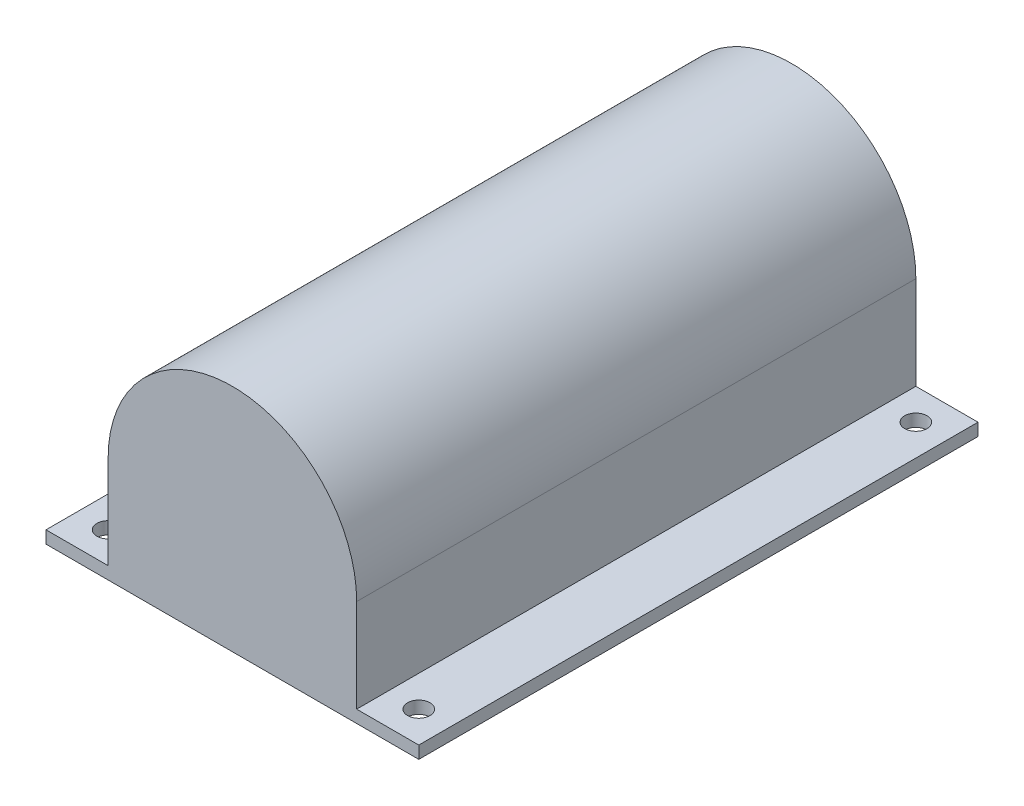
SolidWorks part; units mm, degrees
ref_plane "Front Plane" through (0, 0, 0) normal (0, 0, 1) x (1, 0, 0)
ref_plane "Top Plane" through (0, 0, 0) normal (0, 1, 0) x (1, 0, 0)
ref_plane "Right Plane" through (0, 0, 0) normal (1, 0, 0) x (0, 0, -1)
sketch "Sketch1" plane through (0, 0, 0) normal (0, 0, 1) x (1, 0, 0)
  line L0 (38.1, 8.89) -> (38.1, 46.99) construction
  line L1 (0, 0) -> (76.2, 0)
  line L2 (0, 0) -> (0, 2.54)
  line L3 (0, 2.54) -> (12.7, 2.54)
  line L4 (76.2, 0) -> (76.2, 2.54)
  line L5 (12.7, 2.54) -> (12.7, 21.59)
  line L7 (63.5, 21.59) -> (63.5, 2.54)
  line L10 (63.5, 2.54) -> (76.2, 2.54)
  arc A1 (63.5, 21.59) -> (12.7, 21.59) centre (38.1, 21.59) ccw
  point P8 (38.1, 2.54)
  dimension "D5" = 25.4
  dimension "D3" = 19.05
  dimension "D1" = 76.2
  dimension "D2" = 2.54
  dimension "D4" = 38.1
  dimension "D6" = 12.7
  dimension "D7" = 12.7
extrude "Boss-Extrude2" add sketch "Sketch1" along normal blind 114.3
sketch "Sketch2" plane through (0, 2.54, 0) normal (0, 1, 0) x (1, 0, 0)
  line L0 (0, 0) -> (12.7, 0) construction
  line L1 (63.5, 0) -> (76.2, 0) construction
  line L2 (0, -114.3) -> (0, 0) construction
  line L3 (76.2, -114.3) -> (76.2, 0) construction
  line L4 (63.5, -114.3) -> (76.2, -114.3) construction
  line L5 (0, -114.3) -> (12.7, -114.3) construction
  circle A0 centre (6.35, -6.35) radius 2.286
  circle A1 centre (69.85, -6.35) radius 2.286
  circle A2 centre (69.85, -107.95) radius 2.286
  circle A3 centre (6.35, -107.95) radius 2.286
  point P18 (6.35, -6.35)
  dimension "D1" = 4.572
  dimension "D2" = 6.35
  dimension "D3" = 6.35
  dimension "D4" = 6.35
  dimension "D5" = 6.35
  dimension "D6" = 6.35
  dimension "D7" = 6.35
  dimension "D8" = 6.35
  dimension "D9" = 6.35
extrude "Cut-Extrude1" cut sketch "Sketch2" against normal through all
sketch "Sketch4" plane through (0, 0, 0) normal (0, 0, -1) x (-1, 0, 0)
  line L1 (0, 2.54) -> (-12.7, 2.54) construction
  line L2 (-60.96, 2.54) -> (-15.24, 2.54)
  line L3 (-15.24, 2.54) -> (-15.24, 21.59)
  line L5 (-60.96, 21.59) -> (-60.96, 2.54)
  line L6 (0, 0) -> (-76.2, 0) construction
  arc A0 (-15.24, 21.59) -> (-60.96, 21.59) centre (-38.1, 21.59) ccw
  point P5 (-38.1, 0)
  dimension "D1" = 2.54
  dimension "D2" = 2.54
  dimension "D3" = 2.54
  dimension "D4" = 19.05
  dimension "D5" = 2.54
extrude "Cut-Extrude2" cut sketch "Sketch4" against normal blind 114.046
sketch "Sketch5" plane through (0, 0, 0) normal (0, -1, 0) x (-1, 0, 0)
  line L0 (-6.35, -107.95) -> (-6.35, -6.35) construction
  line L1 (0, -114.3) -> (-76.2, -114.3) construction
  circle A0 centre (-6.35, -88.9) radius 2.5
  circle A1 centre (-6.35, -78.74) radius 2.5
  circle A2 centre (-6.35, -68.58) radius 2.5
  circle A3 centre (-6.35, -58.42) radius 2.5
  dimension "D2" = 5
  dimension "D5" = 10.16
  dimension "D1" = 10.16
  dimension "D3" = 25.4
  dimension "D4" = 10.16
extrude "Cut-Extrude3" cut sketch "Sketch5" against normal through all
sketch "Sketch7" plane through (0, 2.54, 0) normal (0, 1, 0) x (1, 0, 0)
  line L0 (0, -114.3) -> (0, 0) construction
  line L1 (0, 0) -> (12.7, 0) construction
  circle A0 centre (6.35, -25.4) radius 3.175
  dimension "D1" = 6.35
  dimension "D2" = 6.35
  dimension "D3" = 25.4
extrude "Cut-Extrude4" cut sketch "Sketch7" against normal through all
